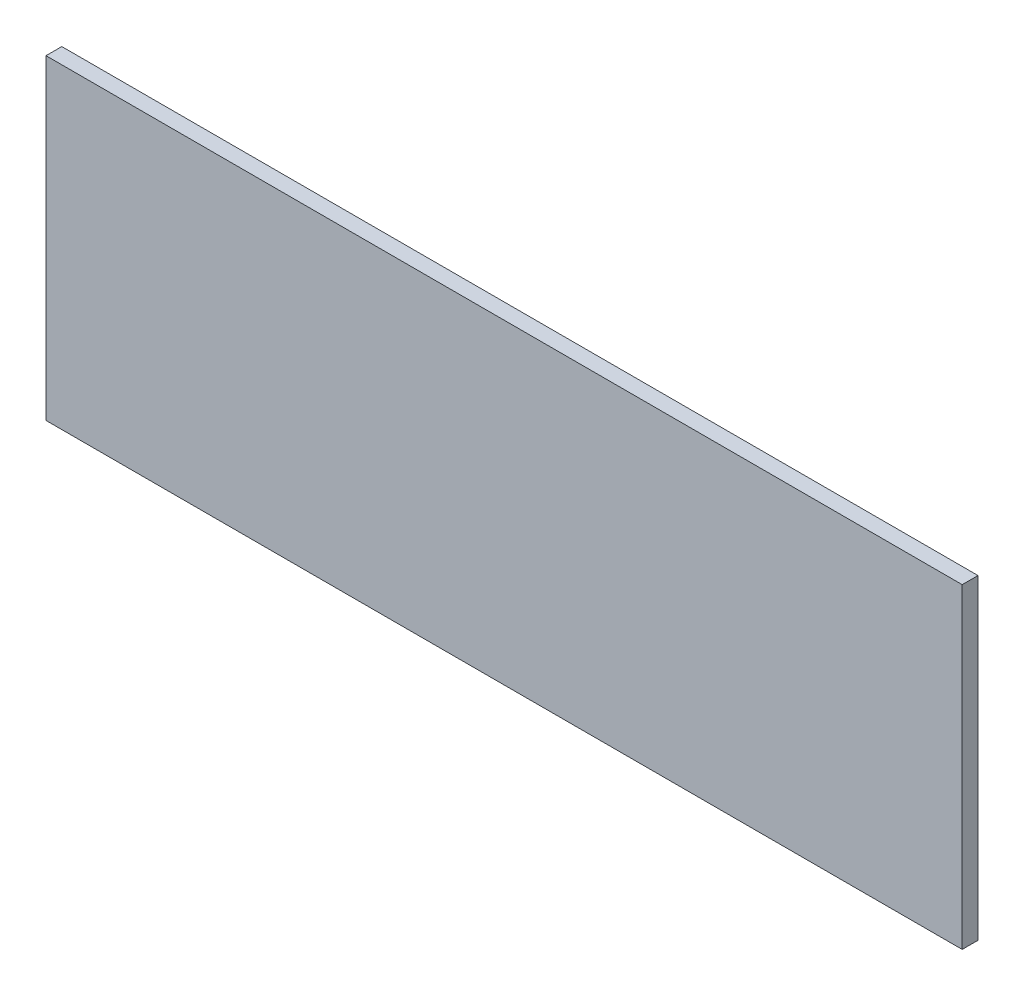
SolidWorks part; units mm, degrees
material "Perspex (TM) GS Acrylic Cast Sheet"
ref_plane "Ebene vorne" through (0, 0, 0) normal (0, 0, 1) x (1, 0, 0)
ref_plane "Ebene oben" through (0, 0, 0) normal (0, 1, 0) x (1, 0, 0)
ref_plane "Ebene rechts" through (0, 0, 0) normal (1, 0, 0) x (0, 0, -1)
sketch "Skizze1" plane through (0, 0, 0) normal (0, 0, 1) x (1, 0, 0)
  line L1 (-145, 50) -> (145, 50)
  line L2 (-145, 50) -> (-145, -50)
  line L3 (-145, -50) -> (145, -50)
  line L4 (145, 50) -> (145, -50)
  line L5 (-145, 50) -> (145, -50) construction
  line L6 (-145, -50) -> (145, 50) construction
  point P0 (0, 0)
  dimension "D1" = 290
  dimension "D2" = 100
extrude "Aufsatz-Linear austragen1" add sketch "Skizze1" along normal blind 5
